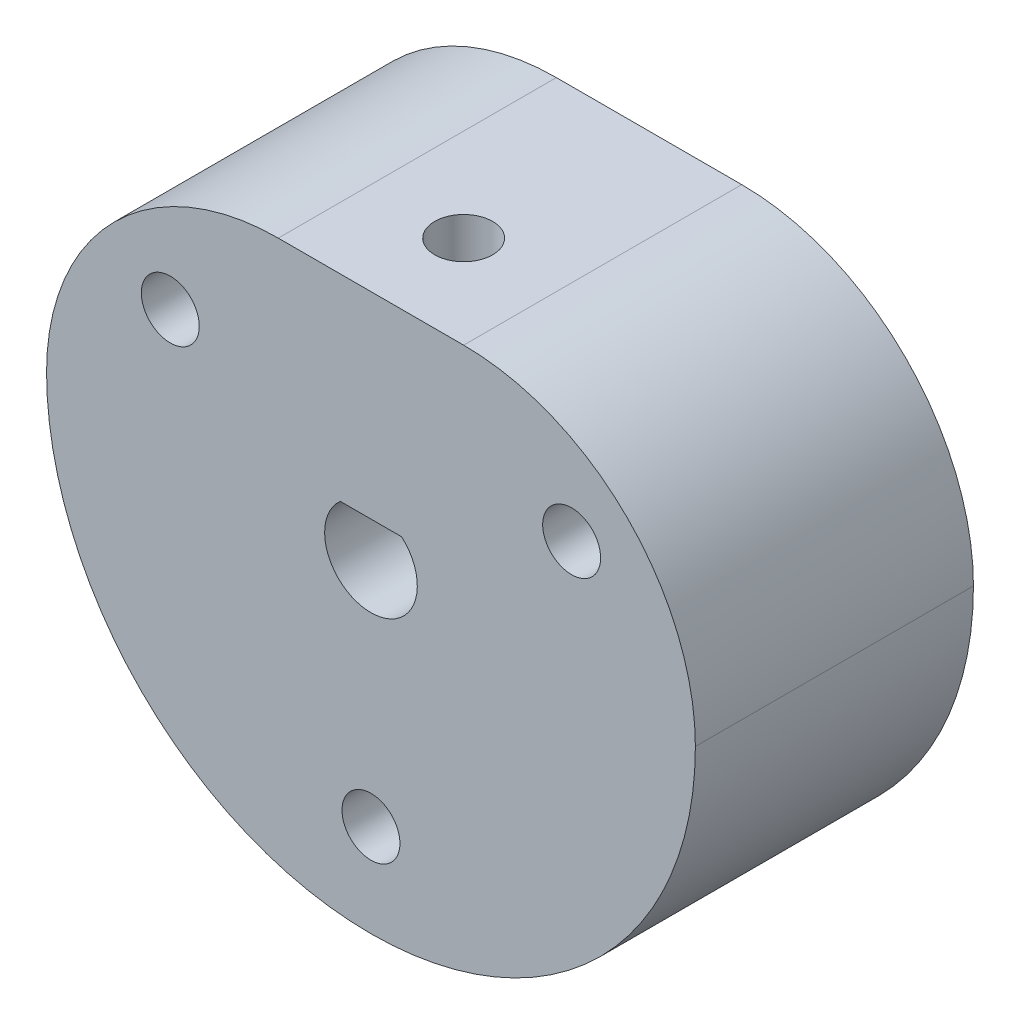
SolidWorks part; units mm, degrees
material "ABS"
ref_plane "正面" through (0, 0, 0) normal (0, 0, 1) x (1, 0, 0)
ref_plane "平面" through (0, 0, 0) normal (0, 1, 0) x (1, 0, 0)
ref_plane "右側面" through (0, 0, 0) normal (1, 0, 0) x (0, 0, -1)
sketch "ｽｹｯﾁ1" plane through (0, 0, 0) normal (0, 0, 1) x (1, 0, 0)
  line L0 (-1.3229, 1.5) -> (1.3229, 1.5)
  line L1 (-9.798, 10) -> (9.798, 10)
  arc A0 (-9.798, 10) -> (9.798, 10) centre (0, 0) ccw
  circle A1 centre (0, 0) radius 10 construction
  circle A2 centre (-8.6603, 5) radius 1.25
  circle A6 centre (8.6603, 5) radius 1.25
  circle A7 centre (0, -10) radius 1.25
  arc A9 (-1.3229, 1.5) -> (1.3229, 1.5) centre (0, 0) ccw
  point P15 (0, 0)
  dimension "D1" = 28
  dimension "D2" = 20
  dimension "D3" = 2.5
  dimension "D5" = 4
  dimension "D6" = 1.5
  dimension "D4" = 3
extrude "ﾎﾞｽ - 押し出し1" add sketch "ｽｹｯﾁ1" along normal blind 12
sketch "ｽｹｯﾁ3" plane through (0, 10, 0) normal (0, 1, 0) x (1, 0, 0)
  line L0 (-9.798, -8) -> (9.798, -8) construction
  line L3 (9.798, -12) -> (-9.798, -12) construction
  line L4 (-9.798, -12) -> (-9.798, 0) construction
  line L5 (9.798, -12) -> (9.798, 0) construction
  circle A0 centre (0, -8) radius 1.25
  point P2 (0, 0)
  point P5 (-9.798, -8)
  point P10 (-5.5852, -8)
  point P11 (0, 0)
  point P12 (9.798, -8)
  dimension "D1" = 2.5
  dimension "D2" = 4
extrude "ｶｯﾄ - 押し出し1" cut sketch "ｽｹｯﾁ3" against normal up to surface (8.5 mm away) up to face at (0, 1.5, 6)
fillet "ﾌｨﾚｯﾄ1" radius 10 2 edges at (-9.798, 10, 6) (9.798, 10, 6)
